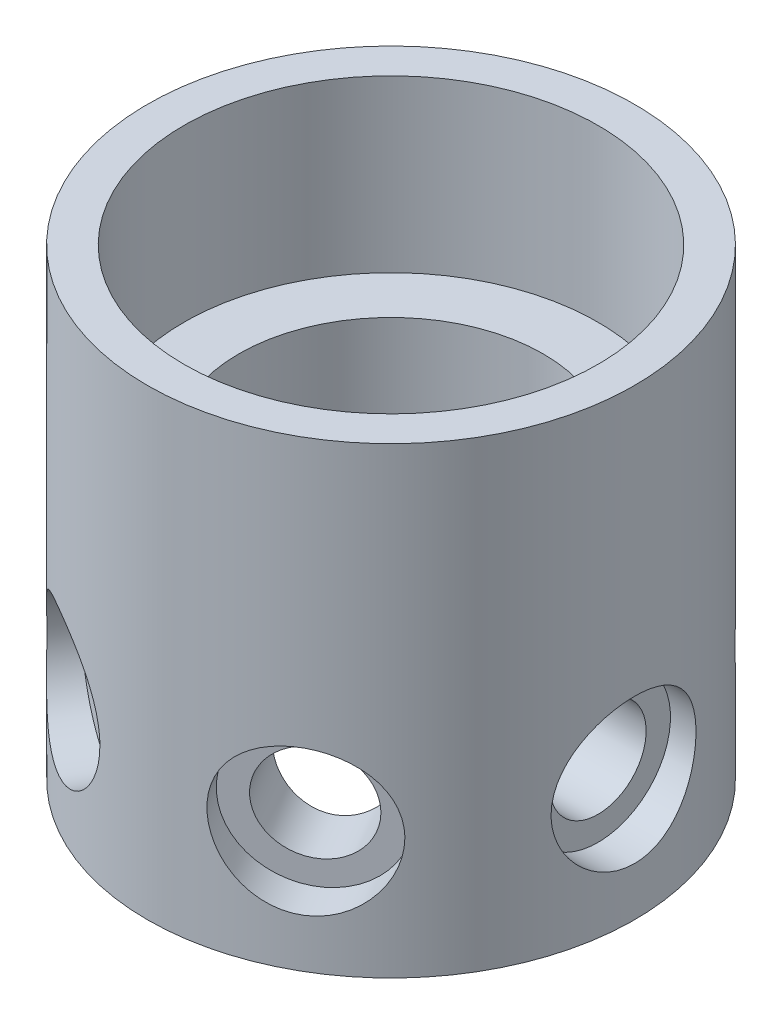
SolidWorks part; units mm, degrees
ref_plane "Front Plane" through (0, 0, 0) normal (0, 0, 1) x (1, 0, 0)
ref_plane "Top Plane" through (0, 0, 0) normal (0, 1, 0) x (1, 0, 0)
ref_plane "Right Plane" through (0, 0, 0) normal (1, 0, 0) x (0, 0, -1)
sketch "Sketch1" plane through (0, 0, 0) normal (0, 1, 0) x (1, 0, 0)
  circle A0 centre (0, 0) radius 20
  dimension "D1" = 40
extrude "Boss-Extrude1" add sketch "Sketch1" along normal blind 38
sketch "Sketch2" plane through (0, 38, 0) normal (0, 1, 0) x (1, 0, 0)
  circle A0 centre (0, 0) radius 12.5
  dimension "D1" = 25
extrude "Cut-Extrude1" cut sketch "Sketch2" against normal blind 38
sketch "Sketch3" plane through (0, 38, 0) normal (0, 1, 0) x (1, 0, 0)
  circle A0 centre (0, 0) radius 17
  dimension "D1" = 34
extrude "Cut-Extrude2" cut sketch "Sketch3" against normal blind 14
sketch "Sketch7" plane through (0, 0, 0) normal (0, 0, 1) x (1, 0, 0)
  line L0 (-17, 6) -> (17, 6)
  line L1 (17, 6) -> (17, 13.9) construction
  line L2 (17, 13.9) -> (-17, 13.9) construction
  line L3 (-17, 13.9) -> (-17, 6) construction
  line L4 (-20, 4) -> (-20, 9.95)
  line L5 (20, 4) -> (20, 9.95)
  line L6 (0, 0) -> (0, 6) construction
  line L7 (-17, 13.9) -> (-17, 15.9) construction
  line L9 (-17, 15.9) -> (-20, 15.9) construction
  line L11 (-20, 38) -> (-20, 0) construction
  line L12 (-20, 15.9) -> (-20, 4) construction
  line L13 (17, 9.95) -> (-17, 9.95) construction
  line L14 (-17, 6) -> (-17, 4)
  line L15 (-17, 4) -> (-20, 4)
  line L16 (17, 6) -> (17, 4)
  line L17 (17, 4) -> (20, 4)
  line L18 (20, 15.9) -> (20, 4) construction
  line L19 (17, 15.9) -> (20, 15.9) construction
  line L20 (17, 13.9) -> (17, 15.9) construction
  line L21 (-20, 9.95) -> (20, 9.95)
  point P16 (-20, 9.95)
  dimension "D1" = 34
  dimension "D2" = 7.9
  dimension "D3" = 6
  dimension "D4" = 2
revolve "Cut-Revolve4" cut sketch "Sketch7" angle 360 about L21
sketch "Sketch8" plane through (0, 0, 0) normal (0, -1, 0) x (1, 0, 0)
  line L0 (20, 0) -> (-20, 0) construction
  line L1 (-10, -17.3205) -> (10, 17.3205) construction
  line L2 (10, -17.3205) -> (-10, 17.3205)
  circle A0 centre (0, 0) radius 20 construction
  point P7 (0, 0)
  point P11 (0, 0)
  point P12 (10.4829, -17.0326)
  dimension "D1" = 60
  dimension "D2" = 0
  dimension "D3" = 0
  dimension "D4" = 60
sketch "Sketch9" plane through (0, 38, 0) normal (0, 1, 0) x (1, 0, 0)
  line L0 (10, 17.3205) -> (-10, -17.3205)
  line L1 (-10, 17.3205) -> (10, -17.3205) construction
ref_plane "Plane2" through (0, 0, 0) normal (0.866, 0, -0.5) x (-0.5, 0, -0.866)
sketch "Sketch10" plane through (0, 0, 0) normal (0.866, 0, -0.5) x (-0.5, 0, -0.866)
  line L0 (-17, 6) -> (17, 6)
  line L1 (17, 6) -> (17, 13.9) construction
  line L2 (17, 13.9) -> (-17, 13.9) construction
  line L3 (-17, 13.9) -> (-17, 6) construction
  line L4 (-20, 4) -> (-20, 9.95)
  line L5 (20, 4) -> (20, 9.95)
  line L6 (0, 0) -> (0, 6) construction
  line L7 (-17, 13.9) -> (-17, 15.9) construction
  line L8 (-17, 15.9) -> (-20, 15.9) construction
  line L9 (-20, 15.9) -> (-20, 4) construction
  line L10 (17, 9.95) -> (-17, 9.95) construction
  line L11 (-17, 6) -> (-17, 4)
  line L12 (-17, 4) -> (-20, 4)
  line L13 (17, 6) -> (17, 4)
  line L14 (17, 4) -> (20, 4)
  line L15 (20, 15.9) -> (20, 4) construction
  line L16 (17, 15.9) -> (20, 15.9) construction
  line L17 (17, 13.9) -> (17, 15.9) construction
  line L18 (-20, 9.95) -> (20, 9.95)
  point P12 (-21.7134, 9.95)
  point P19 (0, 0)
  dimension "D1" = 34
  dimension "D2" = 6
  dimension "D3" = 2
  dimension "D4" = 40
  dimension "D5" = 3.95
revolve "Cut-Revolve5" cut sketch "Sketch10" angle 360 about L18
ref_plane "Plane3" through (0, 0, 0) normal (0.866, 0, 0.5) x (0.5, 0, -0.866)
sketch "Sketch11" plane through (0, 0, 0) normal (0.866, 0, 0.5) x (0.5, 0, -0.866)
  line L0 (-17, 6) -> (17, 6)
  line L1 (17, 6) -> (17, 13.9) construction
  line L2 (17, 13.9) -> (-17, 13.9) construction
  line L3 (-17, 13.9) -> (-17, 6) construction
  line L4 (-20, 4) -> (-20, 9.95)
  line L5 (20, 4) -> (20, 9.95)
  line L6 (0, 0) -> (0, 6) construction
  line L7 (-17, 13.9) -> (-17, 15.9) construction
  line L8 (-17, 15.9) -> (-20, 15.9) construction
  line L9 (-20, 15.9) -> (-20, 4) construction
  line L10 (17, 9.95) -> (-17, 9.95) construction
  line L11 (-17, 6) -> (-17, 4)
  line L12 (-17, 4) -> (-20, 4)
  line L13 (17, 6) -> (17, 4)
  line L14 (17, 4) -> (20, 4)
  line L15 (20, 15.9) -> (20, 4) construction
  line L16 (17, 15.9) -> (20, 15.9) construction
  line L17 (17, 13.9) -> (17, 15.9) construction
  line L18 (-20, 9.95) -> (20, 9.95)
  point P12 (-20, 9.95)
  point P19 (0, 0)
  point P21 (0.4028, 0.7312)
  dimension "D1" = 34
  dimension "D2" = 6
  dimension "D3" = 2
  dimension "D4" = 40
  dimension "D5" = 3.95
revolve "Cut-Revolve6" cut sketch "Sketch11" angle 360 about L18
